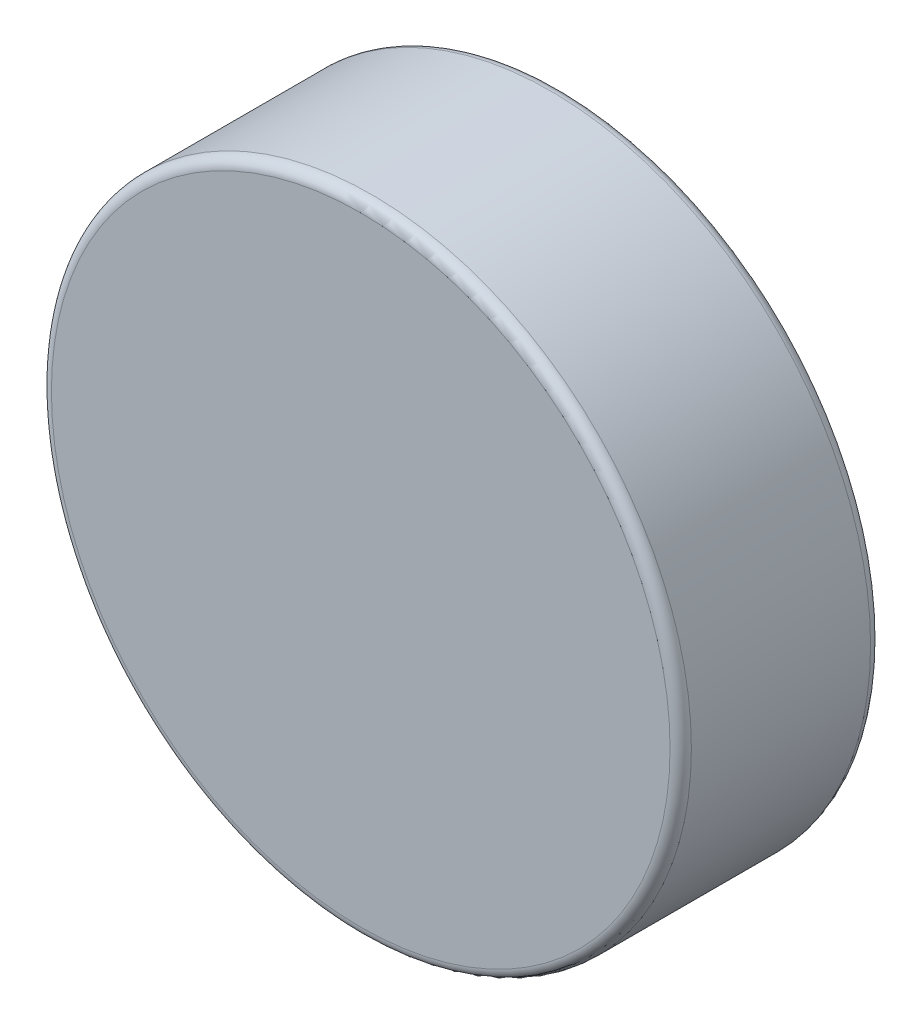
SolidWorks part; units mm, degrees
ref_plane "前视基准面" through (0, 0, 0) normal (0, 0, 1) x (1, 0, 0)
ref_plane "上视基准面" through (0, 0, 0) normal (0, 1, 0) x (1, 0, 0)
ref_plane "右视基准面" through (0, 0, 0) normal (1, 0, 0) x (0, 0, -1)
other "Configuration Table"
sketch "草图1" plane through (0, 0, 0) normal (0, 0, 1) x (1, 0, 0)
  circle A0 centre (0, 0) radius 3
  dimension "D1" = 6
extrude "凸台-拉伸1" add sketch "草图1" along normal blind 1.88
fillet "圆角1" radius 0.1 2 edges at (3, 0, 0) (3, 0, 1.88)
